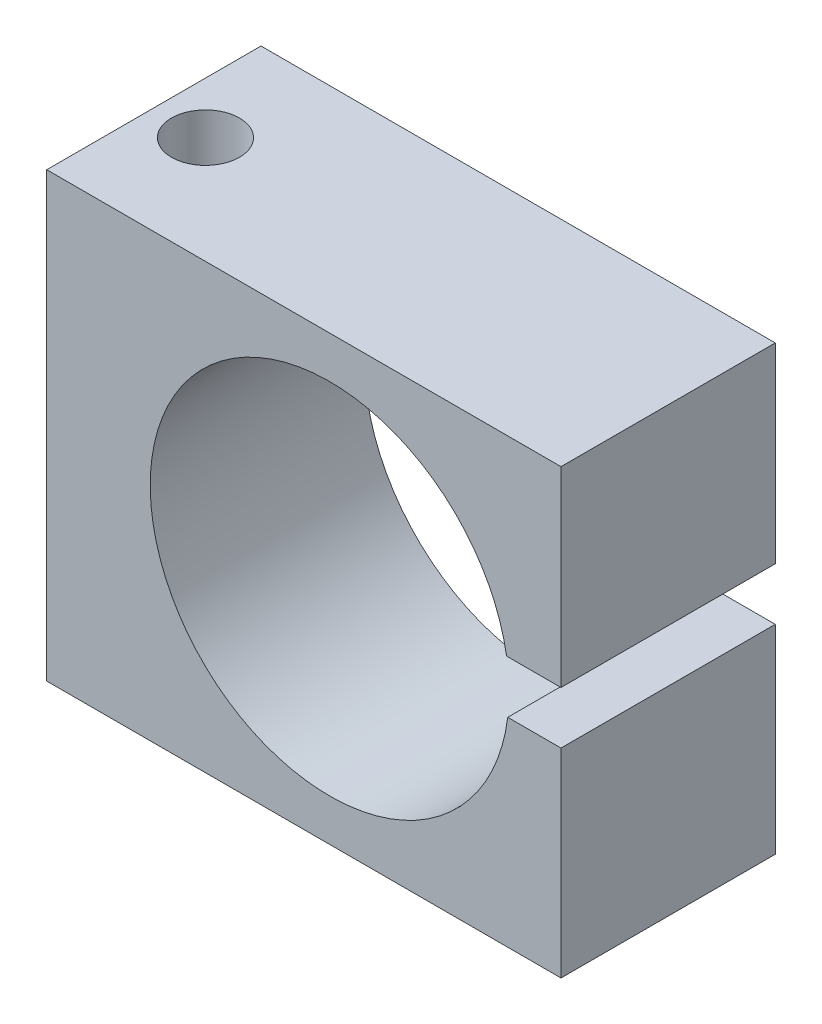
SolidWorks part; units mm, degrees
material "PE Alta densidad"
ref_plane "Alzado" through (0, 0, 0) normal (0, 0, 1) x (1, 0, 0)
ref_plane "Planta" through (0, 0, 0) normal (0, 1, 0) x (1, 0, 0)
ref_plane "Vista lateral" through (0, 0, 0) normal (1, 0, 0) x (0, 0, -1)
ref_plane "Plano1" through (0, 0, 0) normal (0, 0, -1) x (-1, 0, 0)
sketch "Croquis1" plane through (0, 0, 0) normal (0, 0, -1) x (-1, 0, 0)
  line L0 (31.3348, 15.6674) -> (-8.6652, 15.6674)
  line L1 (-8.6652, 15.6674) -> (-8.6652, -15.6674)
  line L2 (-8.6652, -15.6674) -> (31.3348, -15.6674)
  line L3 (31.3348, -15.6674) -> (31.3348, 15.6674)
extrude "Saliente-Extruir1" add sketch "Croquis1" against normal blind 20
sketch "Croquis2" plane through (0, 0, 20) normal (0, 0, 1) x (1, 0, 0)
  line L0 (8.6652, 2.8147) -> (3.617, 2.8147)
  line L1 (3.617, 2.8147) -> (3.617, -2.0789)
  line L2 (3.617, -2.0789) -> (8.6652, -2.0789)
  line L3 (8.6652, -2.0789) -> (8.6652, 2.8147)
extrude "Cortar-Extruir1" cut sketch "Croquis2" against normal through all
hole_wizard "Taladro1" positions "Croquis4" profile "Croquis3" legacy
sketch "Croquis4" plane through (0, 15.6674, 0) normal (0, 1, 0) x (1, 0, 0)
  point P0 (-26.5186, -10)
sketch "Croquis3" plane through (-26.5186, 15.6674, 10) normal (1, 0, 0) x (0, 0, 1)
  line L0 (0, 0) -> (0, 31.3348)
  line L1 (0, 31.3348) -> (3.175, 31.3348)
  line L2 (3.175, 31.3348) -> (3.175, 0)
  line L3 (3.175, 0) -> (0, 0)
  line L4 (0, 110) -> (0, -10) construction
  dimension "Diámetro" = 6.35
  dimension "Profundidad" = 31.3348
hole_wizard "Taladro de margen para M221" positions "Croquis6" profile "Croquis5" hole size "M22" standard "Ansi Metric"
sketch "Croquis6" plane through (0, 0, 0) normal (0, 0, -1) x (-1, 0, 0)
  point P0 (8.7674, 0)
sketch "Croquis5" plane through (-8.7674, 0, 0) normal (1, 0, 0) x (0, 1, 0)
  line L0 (0, 0) -> (0, 20)
  line L1 (0, 20) -> (12.7, 20)
  line L2 (12.7, 20) -> (12.7, 0)
  line L5 (12.7, 0) -> (0, 0)
  line L11 (0, -6.35) -> (0, 107.95) construction
  dimension "Diámetro de taladro hasta el siguiente" = 25.4
  dimension "Profundidad de taladro hasta el siguiente" = 20
sketch "Croquis7" plane through (8.6652, 0, 0) normal (1, 0, 0) x (0, 0, -1)
  line L1 (-20, 15.6674) -> (0, 15.6674)
  line L2 (-20, 15.6674) -> (-20, 2.8147)
  line L3 (-20, 2.8147) -> (0, 2.8147)
  line L4 (0, 15.6674) -> (0, 2.8147)
  line L5 (-20, -2.0789) -> (0, -2.0789)
  line L6 (-20, -2.0789) -> (-20, -15.6674)
  line L7 (-20, -15.6674) -> (0, -15.6674)
  line L8 (0, -2.0789) -> (0, -15.6674)
extrude "Saliente-Extruir2" add sketch "Croquis7" along normal blind 8
sketch "Croquis8" plane through (0, 15.6674, 0) normal (0, 1, 0) x (1, 0, 0)
  line L1 (-31.3348, -20) -> (16.6652, -20)
  line L2 (-31.3348, -20) -> (-31.3348, 0)
  line L3 (-31.3348, 0) -> (16.6652, 0)
  line L4 (16.6652, -20) -> (16.6652, 0)
extrude "Saliente-Extruir3" add sketch "Croquis8" along normal blind 5
sketch "Croquis9" plane through (0, -15.6674, 0) normal (0, -1, 0) x (1, 0, 0)
  circle A0 centre (-26.5186, 10) radius 3.175
extrude "Cortar-Extruir2" cut sketch "Croquis9" against normal blind 43
sketch "Croquis10" plane through (0, -15.6674, 0) normal (0, -1, 0) x (1, 0, 0)
  line L1 (-31.3348, 20) -> (16.6652, 20)
  line L2 (-31.3348, 20) -> (-31.3348, 0)
  line L3 (-31.3348, 0) -> (16.6652, 0)
  line L4 (16.6652, 20) -> (16.6652, 0)
extrude "Saliente-Extruir4" add sketch "Croquis10" along normal blind 5
sketch "Croquis11" plane through (0, 20.6674, 0) normal (0, 1, 0) x (1, 0, 0)
  circle A0 centre (-26.5186, -10) radius 3.175
extrude "Cortar-Extruir3" cut sketch "Croquis11" against normal blind 48
sketch "Croquis12" plane through (0, 0, 20) normal (0, 0, 1) x (1, 0, 0)
  circle A0 centre (-4.9256, 0) radius 16.75
  dimension "D1" = 33.5
extrude "Cortar-Extruir4" cut sketch "Croquis12" against normal blind 48
